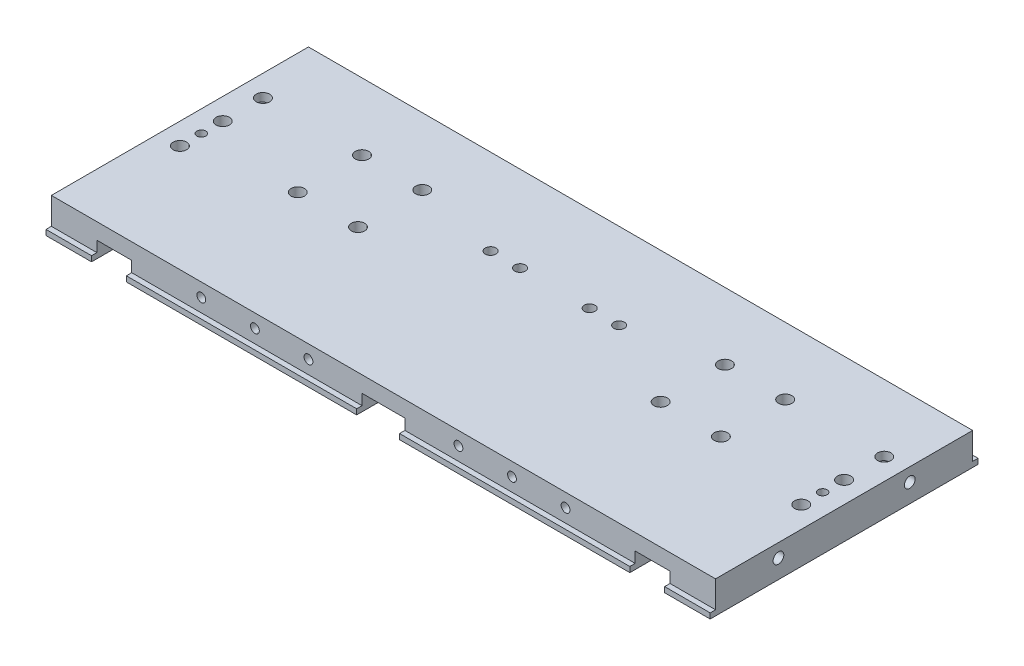
SolidWorks part; units mm, degrees
material "Сталь 45 ГОСТ 1050-88"
ref_plane "Front Plane" through (0, 0, 0) normal (0, 0, 1) x (1, 0, 0)
ref_plane "Top Plane" through (0, 0, 0) normal (0, 1, 0) x (1, 0, 0)
ref_plane "Right Plane" through (0, 0, 0) normal (1, 0, 0) x (0, 0, -1)
sketch "Skizze2" plane through (0, 0, 0) normal (0, 1, 0) x (1, 0, 0)
  line L0 (0, 0) -> (124, 0)
  line L1 (0, 0) -> (-124, 0)
  line L2 (-124, 0) -> (-124, 48)
  line L3 (-124, 0) -> (-124, -48)
  line L4 (-124, -48) -> (124, -48)
  line L5 (124, -48) -> (124, 48)
  line L6 (124, 48) -> (-124, 48)
extrude "Aufsatz-Linear austragen1" add sketch "Skizze2" along normal blind 12 contours L4 L5 L0 L1 L3 | L5 L6 L2 L1 L0
sketch "Skizze3" plane through (0, 0, 48) normal (0, 0, 1) x (1, 0, 0)
  line L0 (-124, 0) -> (-124, 2)
  line L1 (-124, 2) -> (124, 2)
  line L4 (-124, 0) -> (124, 0)
  line L5 (124, 0) -> (124, 12)
  line L6 (124, 12) -> (-124, 12)
  line L7 (-124, 12) -> (-124, 0)
  line L8 (-124, 0) -> (124, 0)
  line L9 (124, 0) -> (124, 12)
  line L10 (124, 12) -> (-124, 12)
  line L11 (-124, 12) -> (-124, 0)
  line M5 (-124, 0) -> (124, 0)
  line M6 (124, 0) -> (124, 12)
  line M8 (-124, 12) -> (-124, 0)
  dimension "D1" = 0
extrude "Aufsatz-Linear austragen2" add sketch "Skizze3" along normal blind 2 contours L1 M8 M5 M6
sketch "Skizze4" plane through (0, 0, -48) normal (0, 0, -1) x (-1, 0, 0)
  line L0 (-124, 0) -> (-124, 2)
  line L1 (-124, 2) -> (124, 2)
  line L4 (-124, 0) -> (124, 0)
  line L5 (124, 0) -> (124, 12)
  line L6 (124, 12) -> (-124, 12)
  line L7 (-124, 12) -> (-124, 0)
  line L8 (-124, 0) -> (124, 0)
  line L9 (124, 0) -> (124, 12)
  line L10 (124, 12) -> (-124, 12)
  line L11 (-124, 12) -> (-124, 0)
  line M5 (-124, 0) -> (124, 0)
  line M6 (124, 0) -> (124, 12)
  line M8 (-124, 12) -> (-124, 0)
  dimension "D1" = 0
extrude "Aufsatz-Linear austragen3" add sketch "Skizze4" along normal blind 2 contours L1 M8 M5 M6
sketch "Skizze5" plane through (0, 0, 0) normal (0, -1, 0) x (1, 0, 0)
  line L0 (124, 49.5) -> (107, 49.5)
  line L1 (-8, 49.5) -> (-94, 49.5)
  line L2 (107, 50) -> (107, -50)
  line L3 (94, 50) -> (94, -50)
  line L4 (124, -50) -> (-124, -50) construction
  line L5 (124, -50) -> (-124, -50)
  line L6 (-124, 50) -> (124, 50) construction
  line L7 (-124, 50) -> (124, 50)
  line L8 (124, -49.5) -> (124, 49.5)
  line L9 (124, 49.5) -> (107, 49.5)
  line L10 (-124, 49.5) -> (-124, -49.5)
  line L11 (-124, -49.5) -> (-107, -49.5)
  line L12 (-124, 49.5) -> (-107, 49.5)
  line L13 (-124, 49.5) -> (-107, 49.5)
  line L14 (-94, 50) -> (-94, -50)
  line L15 (94, 49.5) -> (8, 49.5)
  line L16 (-107, 50) -> (-107, -50)
  line L17 (107, -49.5) -> (124, -49.5)
  line L18 (-8, -50) -> (-8, 50)
  line L19 (-107, 49.5) -> (-124, 49.5)
  line L20 (8, -50) -> (8, 50)
  line L21 (8, -49.5) -> (94, -49.5)
  line L22 (-94, -49.5) -> (-8, -49.5)
  line M8 (-124, -50) -> (124, -50)
extrude "Schnitt-Linear austragen1" cut sketch "Skizze5" against normal blind 6 contours L0 L3 L2 M8 | L20 L9 L18 M8 | L9 L16 L11 L14
sketch "Skizze6" plane through (0, 0, -48) normal (0, 0, -1) x (-1, 0, 0)
  line L1 (-68, 12) -> (-68, 2)
  line L3 (-48, 12) -> (-48, 2)
  line L5 (-28, 12) -> (-28, 2)
  line L6 (0, 0) -> (0, 12)
  line L7 (28, 12) -> (28, 2)
  line L8 (48, 12) -> (48, 2)
  line L9 (68, 12) -> (68, 2)
  line L32 (-107, 2) -> (-107, 6)
  line L33 (-107, 6) -> (-94, 6)
  line L34 (-94, 6) -> (-94, 2)
  line L35 (-94, 2) -> (-8, 2)
  line L36 (-8, 2) -> (-8, 6)
  line L37 (-8, 6) -> (8, 6)
  line L38 (8, 6) -> (8, 2)
  line L39 (8, 2) -> (94, 2)
  line L40 (94, 2) -> (94, 6)
  line L41 (94, 6) -> (107, 6)
  line L42 (107, 6) -> (107, 2)
  line L43 (107, 2) -> (124, 2)
  line L44 (124, 2) -> (124, 12)
  line L45 (124, 12) -> (-124, 12)
  line L46 (-124, 12) -> (-124, 2)
  line L47 (-124, 2) -> (-107, 2)
  point P2 (-68, 7)
  point P17 (-48, 7)
  point P19 (-28, 7)
  point P20 (28, 7)
  point P21 (48, 7)
  point P23 (68, 7)
sketch "Skizze7" plane through (0, 0, 48) normal (0, 0, 1) x (1, 0, 0)
  line L6 (68, 12) -> (68, 2)
  line L7 (48, 12) -> (48, 2)
  line L8 (28, 12) -> (28, 2)
  line L9 (-28, 12) -> (-28, 2)
  line L10 (-68, 12) -> (-68, 2)
  line L11 (-48, 12) -> (-48, 2)
  point P12 (-68, 7)
  point P13 (-48, 7)
  point P14 (-28, 7)
  point P15 (28, 7)
  point P16 (48, 7)
  point P17 (68, 7)
hole_wizard "M4 Gewindebohrung1" positions "3D-Skizze1" profile "Skizze8" tap size "M4" standard "DIN"
sketch3d "3D-Skizze1"
  point P0 (68, 7, -48)
  point P3 (48, 7, -48)
  point P6 (28, 7, -48)
  point P9 (-68, 7, -48)
  point P12 (-48, 7, -48)
  point P15 (-28, 7, -48)
  point P18 (-68, 7, 48)
  point P21 (-48, 7, 48)
  point P24 (-28, 7, 48)
  point P27 (68, 7, 48)
  point P30 (48, 7, 48)
  point P33 (28, 7, 48)
sketch "Skizze8" plane through (68, 7, -48) normal (1, 0, 0) x (0, 1, 0)
  line L0 (0, 0) -> (0, 20.9914)
  line L1 (0, 20.9914) -> (1.65, 20)
  line L2 (1.65, 20) -> (1.65, 0)
  line L5 (1.65, 0) -> (0, 0)
  line L10 (0, 20.9914) -> (-1.65, 20) construction
  line L11 (0, -6.35) -> (0, 107.95) construction
  dimension "Bohrerdurchmesser" = 3.3
  dimension "Bohrungstiefe" = 20
  dimension "Spitzenwinkel" = 118
cosmetic thread "Bohrungsgewinde1" parameters "D1"=12, "D2"=4
cosmetic thread "Bohrungsgewinde2" parameters "D1"=12, "D2"=4
cosmetic thread "Bohrungsgewinde3" parameters "D1"=12, "D2"=4
cosmetic thread "Bohrungsgewinde4" parameters "D1"=12, "D2"=4
cosmetic thread "Bohrungsgewinde5" parameters "D1"=12, "D2"=4
cosmetic thread "Bohrungsgewinde6" parameters "D1"=12, "D2"=4
cosmetic thread "Bohrungsgewinde7" parameters "D1"=12, "D2"=4
cosmetic thread "Bohrungsgewinde8" parameters "D1"=12, "D2"=4
cosmetic thread "Bohrungsgewinde9" parameters "D1"=12, "D2"=4
cosmetic thread "Bohrungsgewinde10" parameters "D1"=12, "D2"=4
cosmetic thread "Bohrungsgewinde11" parameters "D1"=12, "D2"=4
cosmetic thread "Bohrungsgewinde12" parameters "D1"=12, "D2"=4
sketch "Skizze9" plane through (-124, 0, 0) normal (-1, 0, 0) x (0, 0, 1)
  line L0 (0, 0) -> (0, 12)
  line L1 (-24.5, 7) -> (-48, 7)
  line L2 (24.5, 7) -> (24.5, 12)
  line L3 (-24.5, 7) -> (-24.5, 12)
  line L4 (24.5, 7) -> (48, 7)
  line L8 (-50, 0) -> (50, 0)
  line L9 (50, 0) -> (50, 2)
  line L10 (50, 2) -> (48, 2)
  line L11 (48, 2) -> (48, 12)
  line L12 (48, 12) -> (-48, 12)
  line L13 (-48, 12) -> (-48, 2)
  line L14 (-48, 2) -> (-50, 2)
  line L15 (-50, 2) -> (-50, 0)
  line L16 (-50, 0) -> (50, 0)
  line L17 (50, 0) -> (50, 2)
  line L18 (50, 2) -> (48, 2)
  line L19 (48, 2) -> (48, 12)
  line L20 (48, 12) -> (-48, 12)
  line L21 (-48, 12) -> (-48, 2)
  line L22 (-48, 2) -> (-50, 2)
  line L23 (-50, 2) -> (-50, 0)
  point P9 (24.5, 7)
  dimension "D1" = 0
hole_wizard "Ø4.0 (4) Durchmesser Bohrung1" positions "3D-Skizze2" profile "Skizze10" hole size "Ø4.0" standard "DIN"
sketch3d "3D-Skizze2"
  point P0 (-124, 7, -24.5)
  point P3 (-124, 7, 24.5)
sketch "Skizze10" plane through (-124, 7, -24.5) normal (0, 1, 0) x (0, 0, 1)
  line L0 (0, 0) -> (0, 19.2017)
  line L1 (0, 19.2017) -> (2, 18)
  line L2 (2, 18) -> (2, 0)
  line L5 (2, 0) -> (0, 0)
  line L10 (0, 19.2017) -> (-2, 18) construction
  line L11 (0, -6.35) -> (0, 107.95) construction
  dimension "Bohrerdurchmesser" = 4
  dimension "Bohrungstiefe" = 18
  dimension "Spitzenwinkel" = 118
sketch "Skizze11" plane through (124, 0, 0) normal (1, 0, 0) x (0, 0, -1)
  line L0 (-24.5, 7) -> (-24.5, 12) construction
  line L1 (24.5, 7) -> (24.5, 12) construction
  line L2 (24.5, 7) -> (48, 7) construction
  line L3 (-24.5, 7) -> (-48, 7) construction
  line L4 (-24.5, 7) -> (-24.5, 12)
  line L5 (24.5, 7) -> (24.5, 12)
  line L6 (24.5, 7) -> (48, 7)
  line L7 (-24.5, 7) -> (-48, 7)
  point P7 (-24.5, 7)
  point P8 (24.5, 7)
hole_wizard "Ø4.0 (4) Durchmesser Bohrung2" positions "3D-Skizze3" profile "Skizze12" hole size "Ø4.0" standard "DIN"
sketch3d "3D-Skizze3"
  point P0 (124, 7, 24.5)
  point P3 (124, 7, -24.5)
sketch "Skizze12" plane through (124, 7, 24.5) normal (0, 1, 0) x (0, 0, -1)
  line L0 (0, 0) -> (0, 19.2017)
  line L1 (0, 19.2017) -> (2, 18)
  line L2 (2, 18) -> (2, 0)
  line L5 (2, 0) -> (0, 0)
  line L10 (0, 19.2017) -> (-2, 18) construction
  line L11 (0, -6.35) -> (0, 107.95) construction
  dimension "Bohrerdurchmesser" = 4
  dimension "Bohrungstiefe" = 18
  dimension "Spitzenwinkel" = 118
sketch "Skizze13" plane through (0, 12, 0) normal (0, 1, 0) x (1, 0, 0)
  line L0 (0, -48) -> (0, 48)
  line L1 (-124, 0) -> (124, 0)
  line L2 (116, 48) -> (116, -48)
  line L3 (-116, 48) -> (-116, -48)
  line L4 (-124, -48) -> (124, -48)
  line L5 (124, -48) -> (124, 48)
  line L6 (124, 48) -> (-124, 48)
  line L7 (-124, 48) -> (-124, -48)
  line L8 (-124, -48) -> (124, -48)
  line L9 (124, -48) -> (124, 48)
  line L10 (124, 48) -> (-124, 48)
  line L11 (-124, 48) -> (-124, -48)
  point P12 (-116, 0)
  point P13 (116, 0)
  dimension "D1" = 0
hole_wizard "M4 Gewindebohrung2" positions "3D-Skizze4" profile "Skizze14" tap size "M4" standard "DIN" end condition through all
sketch3d "3D-Skizze4"
  point P0 (-116, 12, 0)
  point P3 (116, 12, 0)
sketch "Skizze14" plane through (-116, 12, 0) normal (1, 0, 0) x (0, 0, 1)
  line L0 (0, 0) -> (0, 12)
  line L1 (0, 12) -> (1.65, 12)
  line L2 (1.65, 12) -> (1.65, 0)
  line L5 (1.65, 0) -> (0, 0)
  line L11 (0, -6.35) -> (0, 107.95) construction
  dimension "Bohrerdurchmesser" = 3.3
  dimension "Bohrungstiefe" = 12
cosmetic thread "Bohrungsgewinde13" parameters "D2"=4
cosmetic thread "Bohrungsgewinde14" parameters "D2"=4
sketch "Skizze15" plane through (0, 12, 0) normal (0, 1, 0) x (1, 0, 0)
  line L1 (124, 48) -> (-124, 48)
  circle A0 centre (-13, 16) radius 2
  circle A1 centre (-24, 16) radius 2
  circle A2 centre (13, 16) radius 2
  circle A3 centre (24, 16) radius 2
extrude "Schnitt-Linear austragen2" cut sketch "Skizze15" against normal through all contours A3 | A0 | A1 | A2
sketch "Skizze16" plane through (0, 12, 0) normal (0, 1, 0) x (1, 0, 0)
  line L2 (124, -48) -> (124, 48)
  line L3 (124, 48) -> (-124, 48)
  line L5 (-124, 48) -> (-124, -48)
  line L6 (101.5, 23) -> (101.5, -1)
  line L7 (101.5, -1) -> (79, -1)
  line L8 (124, 23) -> (101.5, 23)
  line L9 (101.5, 23) -> (101.5, 48)
  line L10 (79, -1) -> (79, 23)
  line L11 (79, 23) -> (101.5, 23)
  line L12 (79, 23) -> (56.5, 23)
  line L13 (56.5, 23) -> (56.5, -1)
  line L14 (56.5, -1) -> (79, -1)
  line L15 (0, 48) -> (0, 13.1123) construction
  line L16 (-56.5, -1) -> (-79, -1)
  line L17 (-56.5, 23) -> (-56.5, -1)
  line L18 (-79, 23) -> (-56.5, 23)
  line L19 (-79, 23) -> (-101.5, 23)
  line L20 (-79, -1) -> (-79, 23)
  line L21 (-101.5, 23) -> (-101.5, 48)
  line L22 (-124, 23) -> (-101.5, 23)
  line L23 (-101.5, -1) -> (-79, -1)
  line L24 (-101.5, 23) -> (-101.5, -1)
  line L25 (-124, -16.8019) -> (-116, -16.8019)
  line L26 (-116, -16.8019) -> (-116, 45.4487)
  line L27 (124, -35.7148) -> (116, -35.7148)
  line L28 (116, -35.7148) -> (116, 45.4487)
  line L29 (-116, 48) -> (-116, 22.3538)
  line L30 (-116, 48) -> (-116, 23)
  line L31 (-116, 20.4487) -> (-116, 8)
  line L32 (-116, 8) -> (-116, -8)
  line L33 (-116, -8) -> (119.1044, -8)
  line L34 (-116, 8) -> (119.1044, 8)
  line L35 (-107.9889, 23) -> (-107.9889, 8)
  point P16 (101.5, -1)
  point P17 (101.5, 23)
  point P18 (79, 23)
  point P19 (79, -1)
  point P20 (56.5, -1)
  point P21 (56.5, 23)
  point P38 (116, 23)
  point P42 (116, 8)
  point P43 (116, -8)
hole_wizard "Ø5.0 (5) Durchmesser Bohrung1" positions "3D-Skizze7" profile "Skizze19" hole size "Ø5.0" standard "DIN" end condition through all
sketch3d "3D-Skizze7"
  point P0 (-116, 12, -23)
  point P3 (-116, 12, 8)
  point P6 (-116, 12, -8)
  point P9 (-79, 12, 1)
  point P12 (-56.5, 12, 1)
  point P15 (-56.5, 12, -23)
  point P18 (-79, 12, -23)
  point P21 (79, 12, -23)
  point P24 (56.5, 12, -23)
  point P27 (56.5, 12, 1)
  point P30 (79, 12, 1)
  point P33 (116, 12, 8)
  point P36 (116, 12, -8)
  point P39 (116, 12, -23)
sketch "Skizze19" plane through (-116, 12, -23) normal (1, 0, 0) x (0, 0, 1)
  line L0 (0, 0) -> (0, 12)
  line L1 (0, 12) -> (2.5, 12)
  line L2 (2.5, 12) -> (2.5, 0)
  line L5 (2.5, 0) -> (0, 0)
  line L11 (0, -6.35) -> (0, 107.95) construction
  dimension "Bohrerdurchmesser" = 5
  dimension "Bohrungstiefe" = 12
